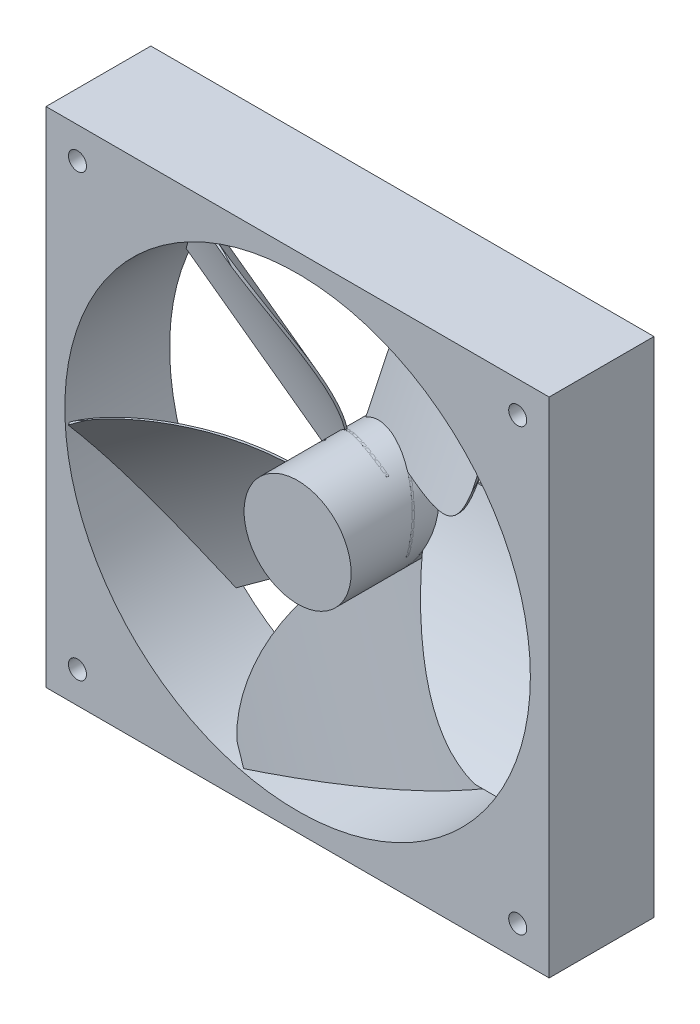
SolidWorks part; units mm, degrees
material "ABS"
ref_plane "Přední rovina" through (0, 0, 0) normal (0, 0, 1) x (1, 0, 0)
ref_plane "Horní rovina" through (0, 0, 0) normal (0, 1, 0) x (1, 0, 0)
ref_plane "Pravá rovina" through (0, 0, 0) normal (1, 0, 0) x (0, 0, -1)
sketch "Skica1" plane through (0, 0, 0) normal (0, 0, 1) x (1, 0, 0)
  line L0 (-60, -60) -> (60, 60) construction
  line L1 (-60, 60) -> (60, 60)
  line L2 (-60, 60) -> (-60, -60)
  line L3 (-60, -60) -> (60, -60)
  line L4 (60, 60) -> (60, -60)
  dimension "D1" = 120
  dimension "D2" = 120
extrude "Přidat vysunutím1" add sketch "Skica1" along normal blind 25
sketch "Skica2" plane through (0, 0, 0) normal (0, 0, 1) x (1, 0, 0)
  line L0 (-52.5, -52.5) -> (52.5, 52.5) construction
  line L1 (-52.5, 52.5) -> (52.5, -52.5) construction
  circle A0 centre (-52.5, 52.5) radius 2.15
  circle A1 centre (52.5, 52.5) radius 2.15
  circle A2 centre (52.5, -52.5) radius 2.15
  circle A3 centre (-52.5, -52.5) radius 2.15
  dimension "D1" = 105
  dimension "D2" = 4.3
extrude "Odebrat vysunutím1" cut sketch "Skica2" along normal through all
sketch "Skica3" plane through (0, 0, 0) normal (0, 0, 1) x (1, 0, 0)
  circle A0 centre (0, 0) radius 55.5163
  circle A1 centre (0, 0) radius 12.7655
extrude "Odebrat vysunutím2" cut sketch "Skica3" along normal through all
sketch "Skica5" plane through (0, 0, 0) normal (1, 0, 0) x (0, 0, -1)
  line L0 (-24, -29.8372) -> (-1, 10) construction
  line L1 (0, -60) -> (0, 60) construction
  line L2 (-25, -60) -> (-25, 60) construction
  line L3 (0, 0) -> (-40.8968, 0) construction
  arc A0 (-1, 10) -> (-24, -29.8372) centre (-87.5555, 33.4147) cw
  dimension "D3" = 60
  dimension "D1" = 1
  dimension "D2" = 1
  dimension "D4" = 3
  dimension "D5" = 10
extrude "Vysunout tenkostěnný1" add sketch "Skica5" along normal up to surface (54.5842 mm away) separate body thin
sketch "Skica6" plane through (0, 0, 0) normal (0, 0, 1) x (1, 0, 0)
  line L0 (46.8167, -29.8372) -> (0, -29.8372) construction
  line L1 (54.5842, 10.1306) -> (0, 10.1306) construction
  line L2 (46.8167, -29.8372) -> (0, -29.8372) construction
  line L3 (0, 10) -> (0, -29.8372) construction
  line L4 (0, -12.7655) -> (0, -29.8372)
  line L5 (46.8167, -29.8372) -> (0, -29.8372)
  arc A0 (46.8167, -29.8372) -> (11.8003, -4.8694) centre (46.8167, 7.2015) cw
  circle A1 centre (0, 0) radius 12.7655 construction
  circle A2 centre (0, 0) radius 12.7655 construction
  arc A3 (0, -12.7655) -> (11.8003, -4.8694) centre (0, 0) ccw
  dimension "D1" = 15
extrude "Odebrat vysunutím9" cut sketch "Skica6" along normal up to surface (11.2792 mm away)
pattern_circular "Kruhové pole1" count 5 over 360 about axis through (0, 0, 0) along (0, 0, 1) of bodies 107
